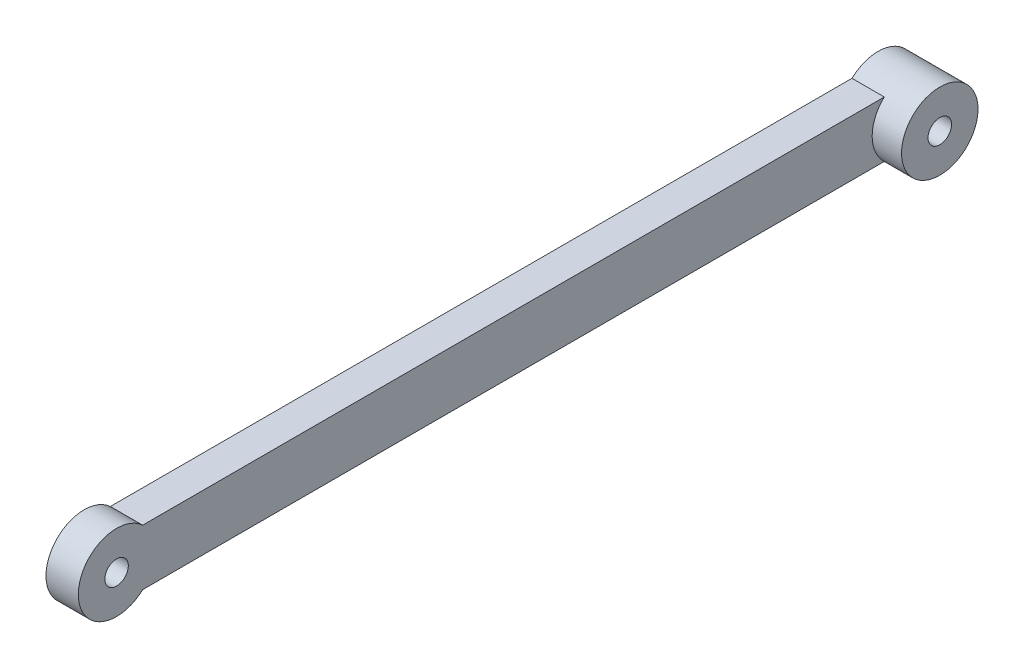
SolidWorks part; units mm, degrees
ref_plane "Plan de face" through (0, 0, 0) normal (0, 0, 1) x (1, 0, 0)
ref_plane "Plan de dessus" through (0, 0, 0) normal (0, 1, 0) x (1, 0, 0)
ref_plane "Plan de droite" through (0, 0, 0) normal (1, 0, 0) x (0, 0, -1)
sketch "Sketch1" plane through (0, 0, 0) normal (1, 0, 0) x (0, 0, -1)
  line L0 (0, 0) -> (135, 0) construction
  line L1 (4.4371, 4.75) -> (130.5629, 4.75)
  line L2 (4.4371, -4.75) -> (130.5629, -4.75)
  arc A0 (4.4371, 4.75) -> (4.4371, -4.75) centre (0, 0) ccw
  circle A1 centre (0, 0) radius 2
  arc A2 (130.5629, -4.75) -> (130.5629, 4.75) centre (135, 0) ccw
  circle A3 centre (135, 0) radius 2
  dimension "D2" = 13
  dimension "D3" = 4
  dimension "D1" = 135
  dimension "D4" = 4.75
extrude "Boss-Extrude1" add sketch "Sketch1" along normal blind 5.5
sketch "Sketch2" plane through (5.5, 0, 0) normal (1, 0, 0) x (0, 0, -1)
  circle A1 centre (135, 0) radius 6.5
  circle A2 centre (135, 0) radius 2 construction
  circle A3 centre (135, 0) radius 2
extrude "Boss-Extrude3" add sketch "Sketch2" along normal blind 5
equation "\"D4@Sketch1\"=9.5/2"
equation "\"Longueur1\"= 135mm"
equation "\"Longueur2\"= 147mm"
equation "\"D1@Sketch1\"=\"Longueur1\""
